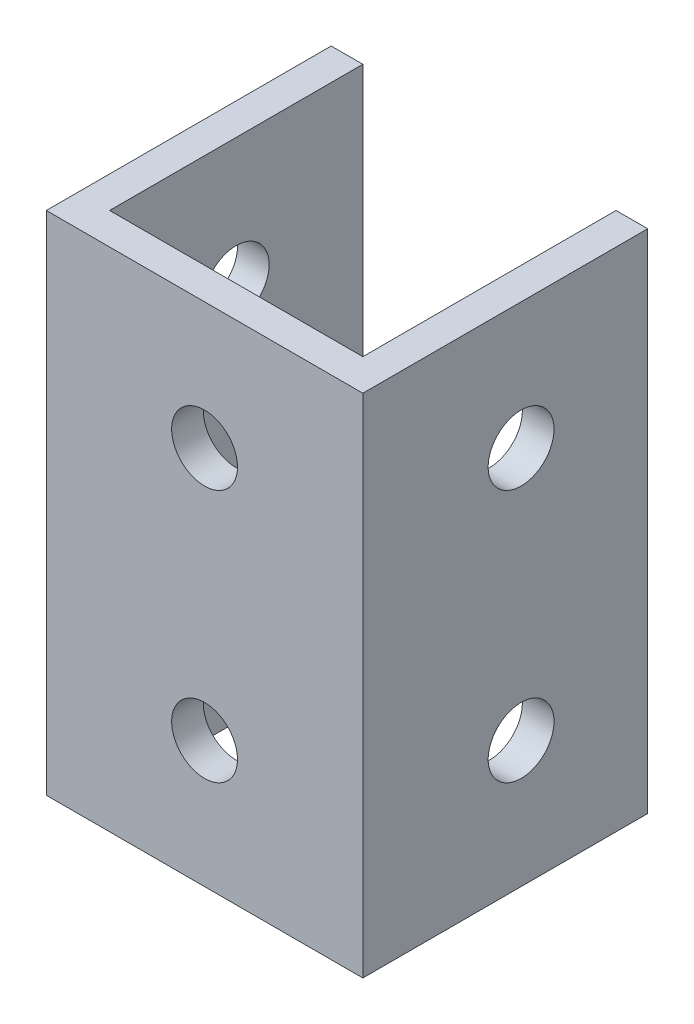
SolidWorks part; units mm, degrees
material "6061 Alloy"
ref_plane "Front Plane" through (0, 0, 0) normal (0, 0, 1) x (1, 0, 0)
ref_plane "Top Plane" through (0, 0, 0) normal (0, 1, 0) x (1, 0, 0)
ref_plane "Right Plane" through (0, 0, 0) normal (1, 0, 0) x (0, 0, -1)
sketch "Sketch1" plane through (0, 0, 0) normal (0, 1, 0) x (1, 0, 0)
  line L0 (0, 0) -> (0, -28.575)
  line L1 (0, -28.575) -> (31.75, -28.575)
  line L2 (31.75, -28.575) -> (31.75, 0)
  line L3 (31.75, 0) -> (28.575, 0)
  line L4 (28.575, 0) -> (28.575, -25.4)
  line L5 (28.575, -25.4) -> (3.175, -25.4)
  line L6 (3.175, -25.4) -> (3.175, 0)
  line L7 (3.175, 0) -> (0, 0)
  dimension "D1" = 28.575
  dimension "D2" = 31.75
  dimension "D3" = 3.175
  dimension "D4" = 3.175
  dimension "D5" = 3.175
extrude "Boss-Extrude1" add sketch "Sketch1" along normal blind 50.8
sketch "Sketch2" plane through (0, 0, 28.575) normal (0, 0, 1) x (1, 0, 0)
  line L0 (15.875, 50.8) -> (15.875, 0) construction
  line L1 (0, 50.8) -> (31.75, 50.8) construction
  line L2 (0, 0) -> (31.75, 0) construction
  circle A0 centre (15.875, 38.1) radius 3.302
  circle A1 centre (15.875, 12.7) radius 3.302
  dimension "D1" = 6.604
  dimension "D2" = 12.7
  dimension "D3" = 12.7
extrude "Cut-Extrude1" cut sketch "Sketch2" against normal up to next
sketch "Sketch3" plane through (31.75, 0, 0) normal (1, 0, 0) x (0, 0, -1)
  line L1 (-28.575, 50.8) -> (0, 50.8) construction
  line L3 (-28.575, 50.8) -> (-28.575, 0) construction
  line L4 (-28.575, 0) -> (0, 0) construction
  circle A0 centre (-12.7, 38.1) radius 3.302
  circle A1 centre (-12.7, 12.7) radius 3.302
  dimension "D1" = 6.604
  dimension "D2" = 12.7
  dimension "D3" = 15.875
  dimension "D4" = 15.875
  dimension "D5" = 12.7
extrude "Cut-Extrude2" cut sketch "Sketch3" against normal through all
